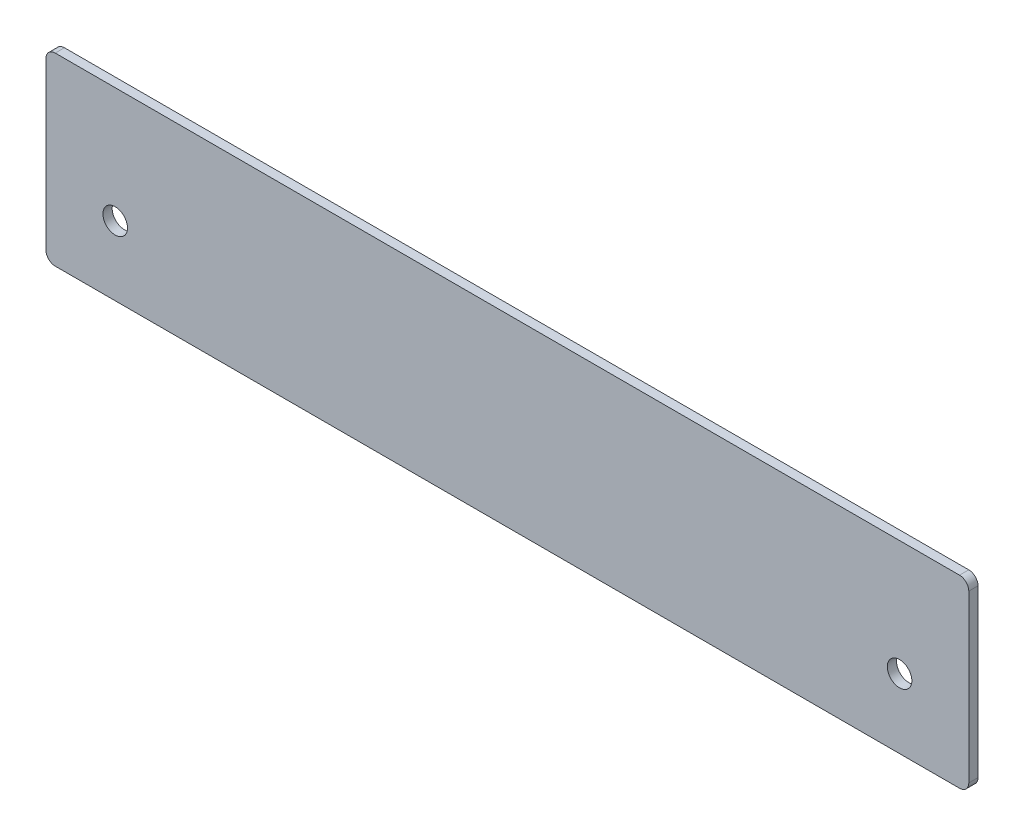
SolidWorks part; units mm, degrees
ref_plane "Front Plane" through (0, 0, 0) normal (0, 0, 1) x (1, 0, 0)
ref_plane "Top Plane" through (0, 0, 0) normal (0, 1, 0) x (1, 0, 0)
ref_plane "Right Plane" through (0, 0, 0) normal (1, 0, 0) x (0, 0, -1)
sketch "Sketch2" plane through (0, 0, 0) normal (0, 0, 1) x (1, 0, 0)
  line L1 (-124.46, 25.4) -> (124.46, 25.4)
  line L2 (-127, 22.86) -> (-127, -22.86)
  line L3 (-124.46, -25.4) -> (124.46, -25.4)
  line L4 (127, 22.86) -> (127, -22.86)
  line L5 (-127, 25.4) -> (127, -25.4) construction
  line L6 (-127, -25.4) -> (127, 25.4) construction
  arc A0 (-127, -22.86) -> (-124.46, -25.4) centre (-124.46, -22.86) ccw
  arc A1 (124.46, -25.4) -> (127, -22.86) centre (124.46, -22.86) ccw
  arc A2 (124.46, 25.4) -> (127, 22.86) centre (124.46, 22.86) cw
  arc A3 (-124.46, 25.4) -> (-127, 22.86) centre (-124.46, 22.86) ccw
  point P0 (0, 0)
  dimension "D3" = 2.54
  dimension "D1" = 50.8
  dimension "D2" = 254
extrude "Boss-Extrude1" add sketch "Sketch2" along normal blind 2.54
sketch "Sketch3" plane through (0, 0, 2.54) normal (0, 0, 1) x (1, 0, 0)
  line L0 (-124.46, -25.4) -> (124.46, -25.4) construction
  line L1 (-127, 22.86) -> (-127, -22.86) construction
  circle A0 centre (-107.95, -6.35) radius 3.3782
  dimension "D1" = 6.7564
  dimension "D2" = 19.05
  dimension "D3" = 19.05
extrude "Cut-Extrude1" cut sketch "Sketch3" against normal through all
sketch "Sketch4" plane through (0, 0, 2.54) normal (0, 0, 1) x (1, 0, 0)
  line L0 (-124.46, -25.4) -> (124.46, -25.4) construction
  line L1 (127, -22.86) -> (127, 22.86) construction
  circle A0 centre (107.95, -6.35) radius 3.3782
  dimension "D1" = 6.7564
  dimension "D2" = 19.05
  dimension "D3" = 19.05
extrude "Cut-Extrude2" cut sketch "Sketch4" against normal through all
